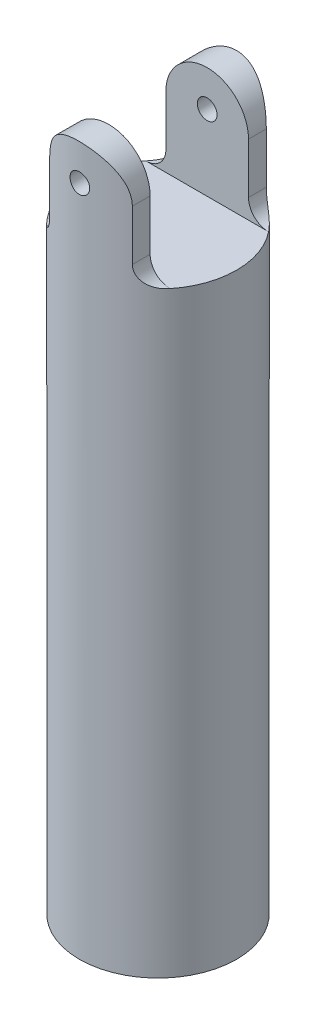
SolidWorks part; units mm, degrees
ref_plane "Front Plane" through (0, 0, 0) normal (0, 0, 1) x (1, 0, 0)
ref_plane "Top Plane" through (0, 0, 0) normal (0, 1, 0) x (1, 0, 0)
ref_plane "Right Plane" through (0, 0, 0) normal (1, 0, 0) x (0, 0, -1)
sketch "Sketch1" plane through (0, 0, 0) normal (0, 1, 0) x (1, 0, 0)
  circle A0 centre (0, 0) radius 6
  dimension "D1" = 12
extrude "Boss-Extrude1" add sketch "Sketch1" along normal blind 12
sketch "Sketch2" plane through (0, 0, 0) normal (1, 0, 0) x (0, 0, -1)
  line L0 (6, 12) -> (-6, 12) construction
  line L1 (-3.75, 12) -> (3.75, 12)
  line L2 (-3.75, 12) -> (-3.75, 3.5)
  line L3 (-3.75, 3.5) -> (3.75, 3.5)
  line L4 (3.75, 12) -> (3.75, 3.5)
  line L5 (-6, 0) -> (6, 0) construction
  point P8 (0, 3.5)
  dimension "D1" = 3.5
  dimension "D2" = 7.5
extrude "Cut-Extrude1" cut sketch "Sketch2" against normal through all both and the other way through all contours L2 L1 L4 L3
sketch "Sketch3" plane through (0, 0, 0) normal (0, 0, 1) x (1, 0, 0)
  line L0 (4.6837, 12) -> (-4.6837, 12) construction
  line L1 (-3.15, 8.85) -> (-3.15, 5)
  line L2 (-4.65, 3.5) -> (-4.6837, 3.5)
  line L3 (-4.6837, 12) -> (-4.6837, 3.5) construction
  line L4 (4.6837, 12) -> (-4.6837, 12)
  line L5 (-4.6837, 12) -> (-4.6837, 3.5)
  line L7 (0, -6.6) -> (0, 6.6) construction
  line L8 (4.6837, 12) -> (4.6837, 3.5)
  line L9 (4.65, 3.5) -> (4.6837, 3.5)
  line L10 (3.15, 8.85) -> (3.15, 5)
  arc A0 (3.15, 8.85) -> (-3.15, 8.85) centre (0, 8.85) ccw
  arc A1 (-3.15, 5) -> (-4.65, 3.5) centre (-4.65, 5) cw
  arc A2 (3.15, 5) -> (4.65, 3.5) centre (4.65, 5) ccw
  circle A4 centre (0, 9.25) radius 0.75
  point P12 (0, 0)
  point P19 (0, 12)
  dimension "D1" = 6.3
  dimension "D2" = 1.5
  dimension "D3" = 2.75
  dimension "D4" = 1.5
extrude "Cut-Extrude2" cut sketch "Sketch3" against normal through all both and the other way through all contours A1 L1 A0 L4 L5 L2 | L10 A2 L9 L8 L4 A0 | A4
sketch "Sketch4" plane through (0, 0, 0) normal (0, -1, 0) x (1, 0, 0)
  line L1 (-0.6, 5) -> (0.6, 5)
  line L2 (-0.6, 5) -> (-0.6, 3.5)
  line L3 (-0.6, 3.5) -> (0.6, 3.5)
  line L4 (0.6, 5) -> (0.6, 3.5)
  line L5 (-0.6, 5) -> (0.6, 3.5) construction
  line L6 (-0.6, 3.5) -> (0.6, 5) construction
  line L7 (5, 1.15) -> (3.5, 1.15)
  line L8 (5, 1.15) -> (5, -1.15)
  line L9 (5, -1.15) -> (3.5, -1.15)
  line L10 (3.5, 1.15) -> (3.5, -1.15)
  line L11 (5, 1.15) -> (3.5, -1.15) construction
  line L12 (5, -1.15) -> (3.5, 1.15) construction
  line L13 (-5, -1.15) -> (-3.5, -1.15)
  line L14 (-5, -1.15) -> (-5, 1.15)
  line L15 (-5, 1.15) -> (-3.5, 1.15)
  line L16 (-3.5, -1.15) -> (-3.5, 1.15)
  line L17 (-5, -1.15) -> (-3.5, 1.15) construction
  line L18 (-5, 1.15) -> (-3.5, -1.15) construction
  line L19 (-0.6, -5) -> (0.6, -5)
  line L20 (-0.6, -5) -> (-0.6, -3.5)
  line L21 (-0.6, -3.5) -> (0.6, -3.5)
  line L22 (0.6, -5) -> (0.6, -3.5)
  line L23 (-0.6, -5) -> (0.6, -3.5) construction
  line L24 (-0.6, -3.5) -> (0.6, -5) construction
  circle A0 centre (0, 0) radius 4.25
  circle A1 centre (0, 0) radius 6 construction
  circle A2 centre (0, 0) radius 6
  point P3 (0, 4.25)
  point P8 (4.25, 0)
  point P13 (-4.25, 0)
  point P18 (0, -4.25)
  circle M26 centre (0, 0) radius 6
  dimension "D4" = 8.5
  dimension "D1" = 2.3
  dimension "D2" = 1.2
  dimension "D3" = 1.5
extrude "Boss-Extrude2" add sketch "Sketch4" along normal blind 42 contours A0 L22 L19 L20 L13 L14 L15 L2 L1 L4 L7 L8 L9 M26
